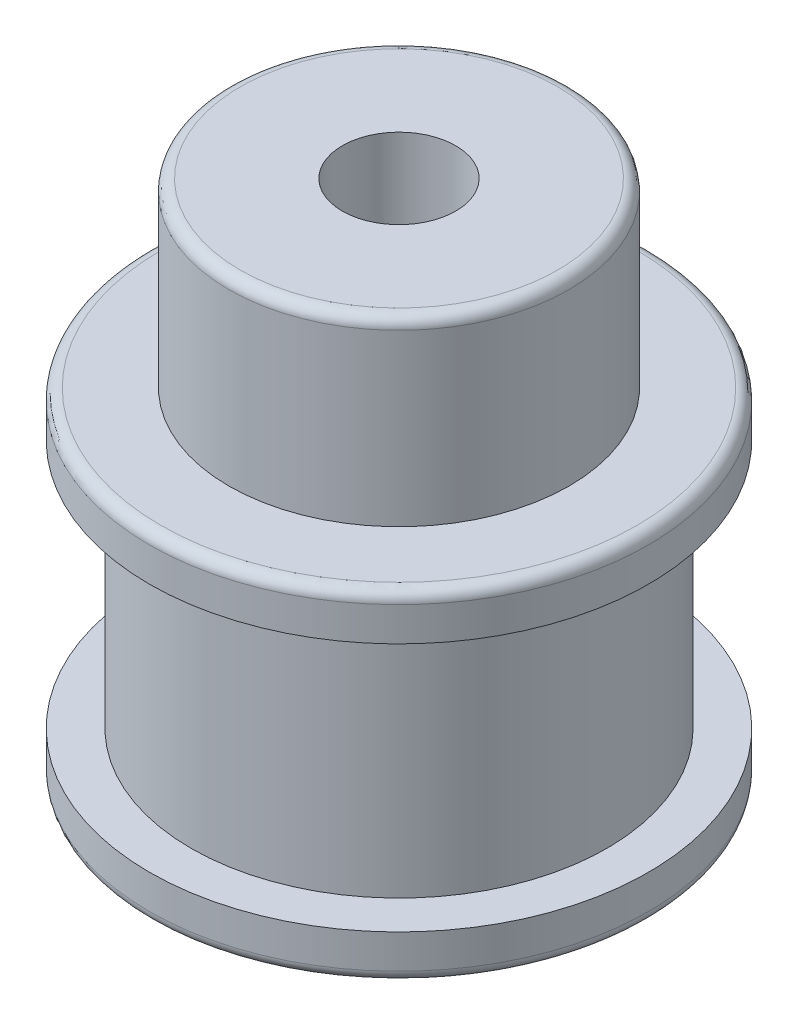
SolidWorks part; units mm, degrees
ref_plane "Front" through (0, 0, 0) normal (0, 0, 1) x (1, 0, 0)
ref_plane "Top" through (0, 0, 0) normal (0, 1, 0) x (1, 0, 0)
ref_plane "Right" through (0, 0, 0) normal (1, 0, 0) x (0, 0, -1)
sketch "草图1" plane through (0, 0, 0) normal (0, 1, 0) x (1, 0, 0)
  circle A0 centre (0, 0) radius 11
  circle A1 centre (0, 0) radius 2.5
  dimension "D1" = 22
  dimension "D2" = 5
extrude "凸台-拉伸1" add sketch "草图1" along normal blind 15
sketch "草图2" plane through (0, 15, 0) normal (0, 1, 0) x (1, 0, 0)
  circle A0 centre (0, 0) radius 2.5
  circle A1 centre (0, 0) radius 7.5
  dimension "D1" = 15
extrude "凸台-拉伸2" add sketch "草图2" along normal blind 8
sketch "草图3" plane through (0, 0, 0) normal (0, 1, 0) x (1, 0, 0)
  circle A0 centre (0, 0) radius 11
  circle A1 centre (0, 0) radius 9.17
  dimension "D1" = 18.34
extrude "切除-拉伸1" cut sketch "草图3" along normal blind 11 from offset 2
fillet "圆角1" radius 0.5 3 edges at (0, 0, 11) (0, 15, 11) (0, 23, 7.5)
